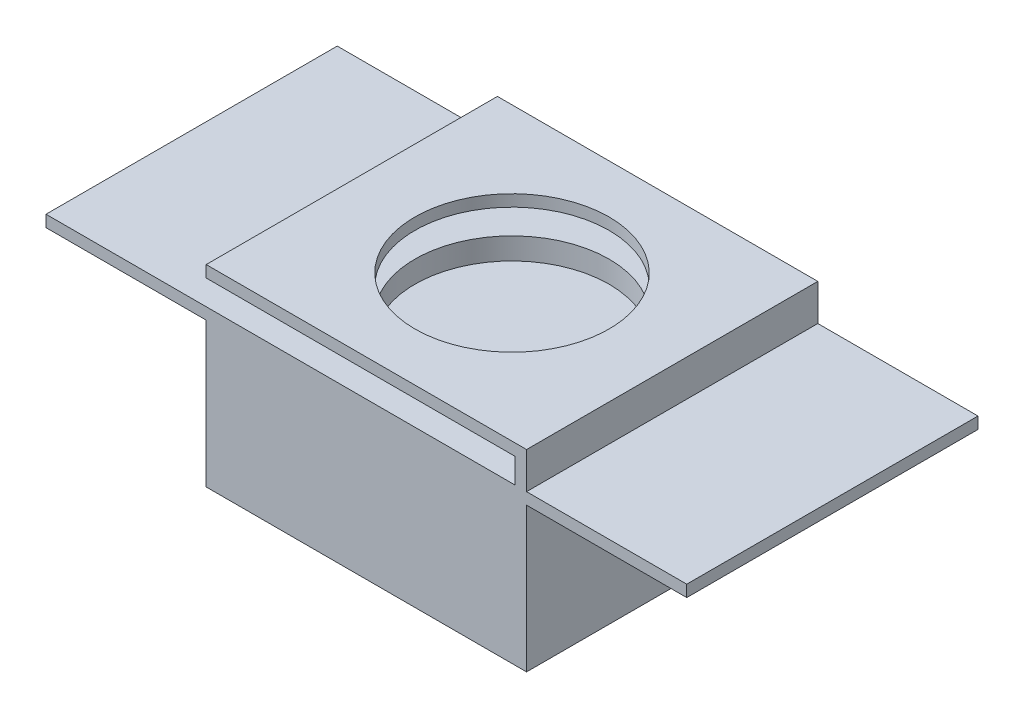
SolidWorks part; units mm, degrees
ref_plane "Front Plane" through (0, 0, 0) normal (0, 0, 1) x (1, 0, 0)
ref_plane "Top Plane" through (0, 0, 0) normal (0, 1, 0) x (1, 0, 0)
ref_plane "Right Plane" through (0, 0, 0) normal (1, 0, 0) x (0, 0, -1)
sketch "Sketch1" plane through (0, 0, 0) normal (0, 0, 1) x (1, 0, 0)
  line L0 (-17.4625, 0) -> (17.4625, 0)
  line L1 (17.4625, 0) -> (17.4625, 15.748)
  line L2 (17.4625, 15.748) -> (34.925, 15.748)
  line L3 (34.925, 15.748) -> (34.925, 17.018)
  line L4 (17.4625, 20.9973) -> (-17.4625, 20.9973)
  line L5 (-34.925, 17.018) -> (-34.925, 15.748)
  line L6 (-34.925, 15.748) -> (-17.4625, 15.748)
  line L7 (-17.4625, 15.748) -> (-17.4625, 0)
  line L8 (-17.4625, 15.748) -> (0, 15.748) construction
  line L9 (0, 15.748) -> (17.4625, 15.748) construction
  line L10 (-34.925, 17.018) -> (-17.4625, 17.018)
  line L11 (-17.4625, 19.7273) -> (-17.4625, 20.9973)
  line L12 (17.4625, 20.9973) -> (17.4625, 17.018)
  line L13 (17.4625, 17.018) -> (34.925, 17.018)
  line L14 (-17.4625, 19.7273) -> (16.1925, 19.7273)
  line L15 (16.1925, 19.7273) -> (16.1925, 17.018)
  line L16 (16.1925, 17.018) -> (-17.4625, 17.018)
  point P18 (16.0096, 17.2009)
  point P19 (17.4625, 19.7273)
  dimension "D1" = 69.85
  dimension "D2" = 15.748
  dimension "D3" = 5.2493
  dimension "D4" = 1.27
extrude "Boss-Extrude1" add sketch "Sketch1" along normal blind 31.75
sketch "Sketch2" plane through (0, 20.9973, 0) normal (0, 1, 0) x (1, 0, 0)
  line L0 (0, 0) -> (0, -31.75) construction
  line L1 (17.4625, -31.75) -> (-17.4625, -31.75) construction
  circle A0 centre (0, -15.875) radius 10.5833
  point P6 (0, 0)
  point P8 (0, -5.2917)
  dimension "D1" = 21.1667
extrude "Cut-Extrude1" cut sketch "Sketch2" against normal blind 6.35
